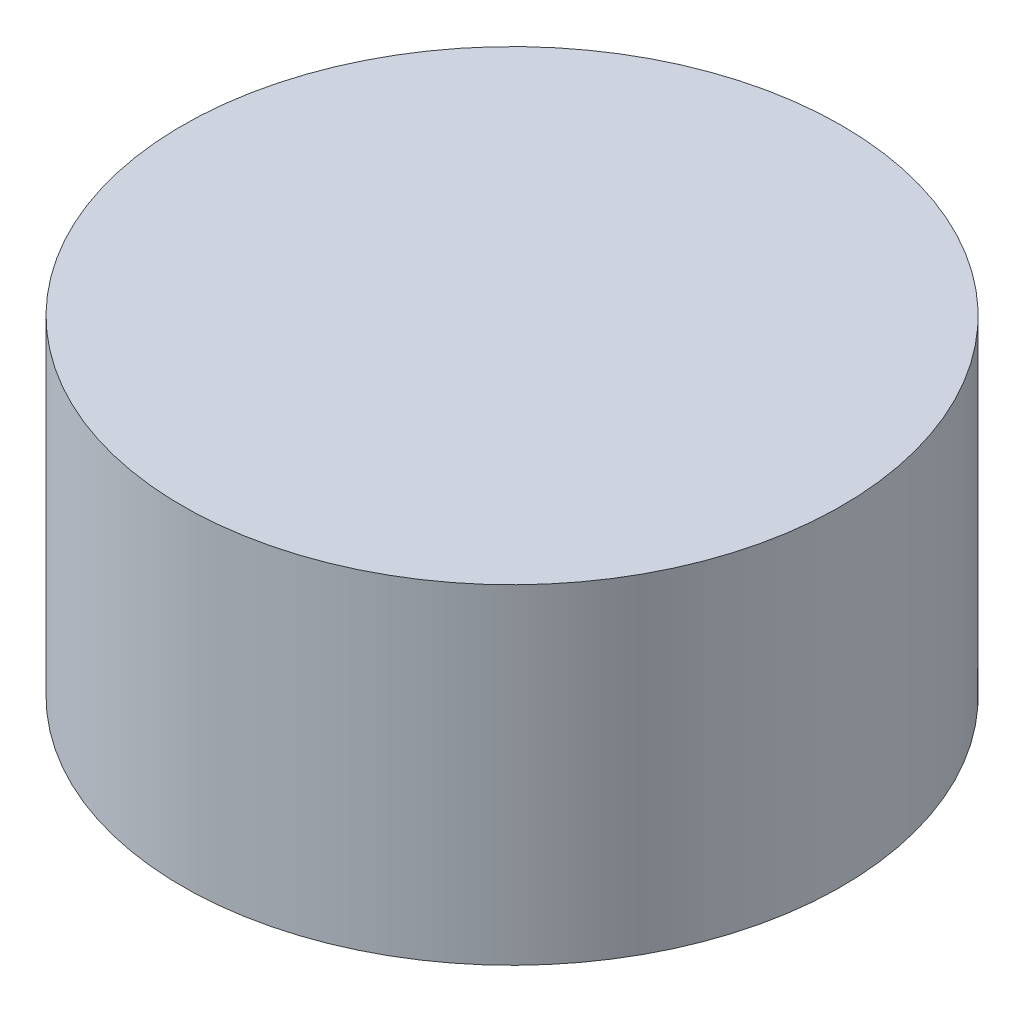
SolidWorks part; units mm, degrees
ref_plane "前视基准面" through (0, 0, 0) normal (0, 0, 1) x (1, 0, 0)
ref_plane "上视基准面" through (0, 0, 0) normal (0, 1, 0) x (1, 0, 0)
ref_plane "右视基准面" through (0, 0, 0) normal (1, 0, 0) x (0, 0, -1)
sketch "草图8" plane through (0, 0, 0) normal (0, 0, 1) x (1, 0, 0)
  line L1 (-50, -50) -> (50, -50)
  line L2 (-50, -50) -> (-50, 50)
  line L3 (-50, 50) -> (50, 50)
  line L4 (50, -50) -> (50, 50)
  line L5 (-50, -50) -> (50, 50) construction
  line L6 (-50, 50) -> (50, -50) construction
  point P0 (0, 0)
  dimension "D1" = 100
revolve "旋转3" add sketch "草图8" angle 360 about L4
